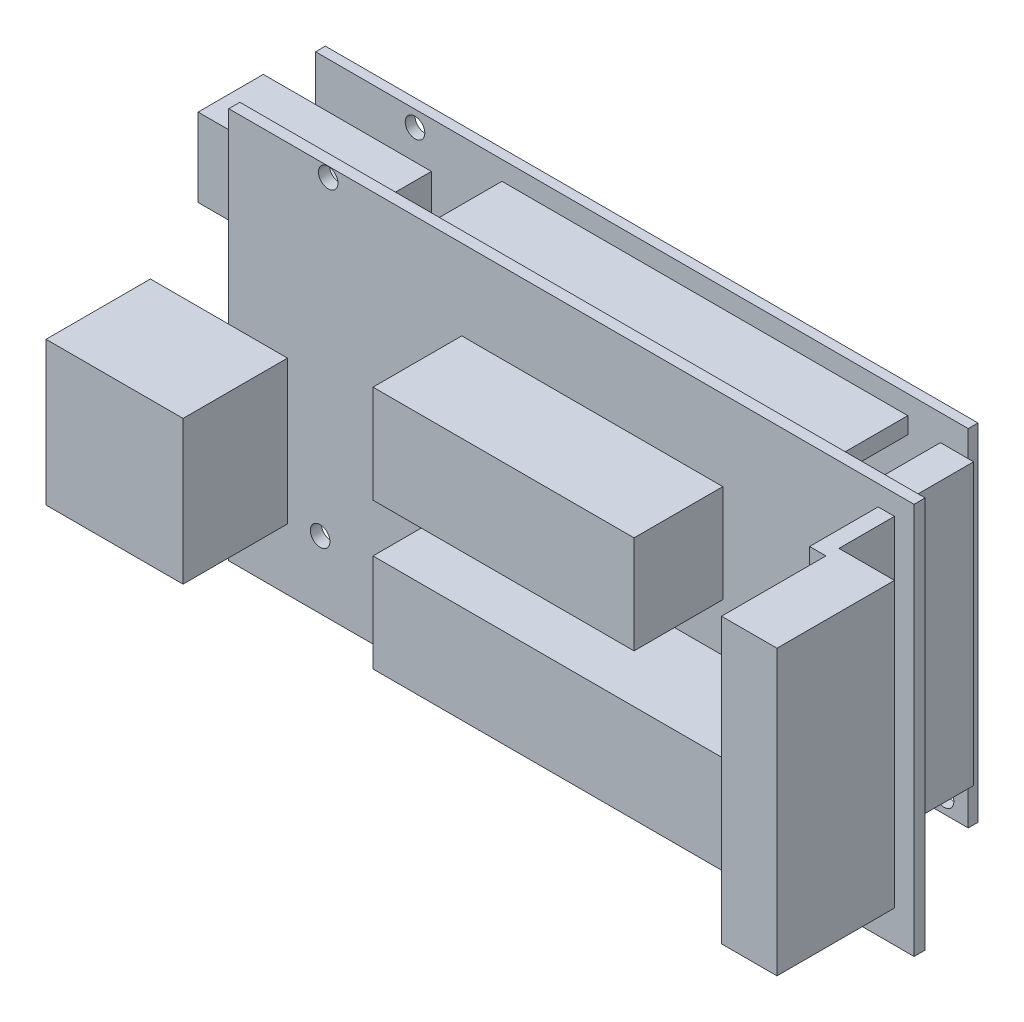
SolidWorks part; units mm, degrees
ref_plane "Plano frontal" through (0, 0, 0) normal (0, 0, 1) x (1, 0, 0)
ref_plane "Plano superior" through (0, 0, 0) normal (0, 1, 0) x (1, 0, 0)
ref_plane "Plano direito" through (0, 0, 0) normal (1, 0, 0) x (0, 0, -1)
sketch "Esboço1" plane through (0, 0, 0) normal (0, 0, 1) x (1, 0, 0)
  line L1 (-52.5, 30) -> (52.5, 30)
  line L2 (-52.5, 30) -> (-52.5, -30)
  line L3 (-52.5, -30) -> (52.5, -30)
  line L4 (52.5, 30) -> (52.5, -30)
  line L5 (-52.5, 30) -> (52.5, -30) construction
  line L6 (-52.5, -30) -> (52.5, 30) construction
  point P0 (0, 0)
  dimension "D1" = 60
  dimension "D2" = 105
extrude "Ressalto-extrusão1" add sketch "Esboço1" along normal blind 1.7
sketch "Esboço2" plane through (0, 0, 1.7) normal (0, 0, 1) x (1, 0, 0)
  line L0 (-52.5, -30) -> (52.5, -30) construction
  line L1 (-16.8, -4.7) -> (43.2, -4.7)
  line L2 (-16.8, -4.7) -> (-16.8, -19.7)
  line L3 (-16.8, -19.7) -> (43.2, -19.7)
  line L4 (43.2, -4.7) -> (43.2, -19.7)
  line L5 (52.5, -30) -> (52.5, 30) construction
  line L7 (-16.8, 2.7) -> (23.2, 2.7)
  line L8 (-16.8, 2.7) -> (-16.8, 17.7)
  line L9 (-16.8, 17.7) -> (23.2, 17.7)
  line L10 (23.2, 2.7) -> (23.2, 17.7)
  dimension "D1" = 60
  dimension "D2" = 15
  dimension "D3" = 10.3
  dimension "D4" = 9.3
  dimension "D5" = 40
  dimension "D6" = 7.4
extrude "Ressalto-extrusão2" add sketch "Esboço2" along normal blind 13.6
sketch "Esboço3" plane through (0, 0, 0) normal (0, 0, -1) x (-1, 0, 0)
  line L0 (52.5, -30) -> (-52.5, -30) construction
  line L1 (52.5, 30.9) -> (-47.5, 30.9)
  line L2 (52.5, 30.9) -> (52.5, -22.1)
  line L3 (52.5, -22.1) -> (-47.5, -22.1)
  line L4 (-47.5, 30.9) -> (-47.5, -22.1)
  line L5 (52.5, 30) -> (52.5, -30) construction
  dimension "D1" = 7.9
  dimension "D2" = 53
  dimension "D3" = 100
extrude "Ressalto-extrusão6" add sketch "Esboço3" along normal blind 1.5 from offset 11.6 separate body
sketch "Esboço4" plane through (0, 0, -11.6) normal (0, 0, 1) x (1, 0, 0)
  line L1 (-23.9415, 27.9898) -> (38.2426, 27.9898)
  line L2 (-23.9415, 27.9898) -> (-23.9415, 25.4498)
  line L3 (-23.9415, 25.4498) -> (38.2426, 25.4498)
  line L4 (38.2426, 27.9898) -> (38.2426, 25.4498)
  line L5 (48.3249, 26.9052) -> (43.2449, 26.9052)
  line L6 (48.3249, 26.9052) -> (48.3249, -16.0526)
  line L7 (48.3249, -16.0526) -> (43.2449, -16.0526)
  line L8 (43.2449, 26.9052) -> (43.2449, -16.0526)
  line L9 (38.2426, -19.9599) -> (-17.8292, -19.9599)
  line L10 (38.2426, -19.9599) -> (38.2426, -17.4199)
  line L11 (38.2426, -17.4199) -> (-17.8292, -17.4199)
  line L12 (-17.8292, -19.9599) -> (-17.8292, -17.4199)
  dimension "D1" = 2.54
  dimension "D2" = 5.08
extrude "Ressalto-extrusão8" add sketch "Esboço4" along normal up to surface (11.6 mm away) up to face at (0, 0, 0)
sketch "Esboço6" plane through (0, 0, 1.7) normal (0, 0, 1) x (1, 0, 0)
  line L1 (-64.5, 1.4) -> (-43.5, 1.4)
  line L2 (-64.5, 1.4) -> (-64.5, -20.6)
  line L3 (-64.5, -20.6) -> (-43.5, -20.6)
  line L4 (-43.5, 1.4) -> (-43.5, -20.6)
  line L5 (-52.5, 30) -> (-52.5, -30) construction
  line L6 (-52.5, 30.9) -> (47.5, 30.9) construction
  dimension "D1" = 22
  dimension "D2" = 29.5
  dimension "D3" = 12
  dimension "D4" = 21
extrude "Ressalto-extrusão9" add sketch "Esboço6" along normal blind 16
sketch "Esboço7" plane through (0, 0, -11.6) normal (0, 0, 1) x (1, 0, 0)
  line L0 (-52.5, 30.9) -> (47.5, 30.9) construction
  line L1 (-34.753, 23.9) -> (-60.5, 23.9)
  line L2 (-34.753, 23.9) -> (-34.753, 11.9)
  line L3 (-34.753, 11.9) -> (-60.5, 11.9)
  line L4 (-60.5, 23.9) -> (-60.5, 11.9)
  line L5 (-52.5, -22.1) -> (-52.5, 30.9) construction
  dimension "D1" = 7
  dimension "D2" = 12
  dimension "D3" = 8
extrude "Ressalto-extrusão10" add sketch "Esboço7" along normal blind 10
sketch "Esboço8" plane through (0, 0, -13.1) normal (0, 0, -1) x (-1, 0, 0)
  line L0 (52.5, -22.1) -> (52.5, 30.9) construction
  line L1 (-47.5, -22.1) -> (52.5, -22.1) construction
  circle A0 centre (37.26, 28.47) radius 1.5
  circle A1 centre (38.5, -19.7) radius 1.5
  circle A2 centre (-43.8, -19.7) radius 1.5
  dimension "D1" = 3
  dimension "D2" = 15.24
  dimension "D3" = 14
  dimension "D4" = 82.3
  dimension "D5" = 2.4
  dimension "D6" = 2.4
  dimension "D7" = 48.17
extrude "Corte-extrusão1" cut sketch "Esboço8" against normal through all
sketch "Esboço9" plane through (0, -30, 0) normal (0, -1, 0) x (1, 0, 0)
  line L0 (49.5, 1.7) -> (49.5, 10.2)
  line L1 (-52.5, 1.7) -> (52.5, 1.7) construction
  line L2 (49.5, 10.2) -> (58, 10.2)
  line L3 (58, 10.2) -> (58, 28.2)
  line L4 (58, 28.2) -> (49.5, 28.2)
  line L5 (49.5, 28.2) -> (49.5, 12.2)
  line L6 (47, 1.7) -> (49.5, 1.7)
  line L7 (49.5, 12.2) -> (47, 12.2)
  line L8 (47, 12.2) -> (47, 1.7)
  line L12 (47.5, -13.1) -> (47.5, -11.6) construction
  dimension "D1" = 8.5
  dimension "D2" = 18
  dimension "D3" = 8.5
  dimension "D4" = 2.5
  dimension "D5" = 0.5
  dimension "D6" = 8.5
  dimension "D7" = 2
extrude "Ressalto-extrusão11" add sketch "Esboço9" against normal up to surface (56.9052 mm away) up to face at (46.1279, 26.9052, -6.96)
sketch "Esboço10" plane through (58, 0, 0) normal (1, 0, 0) x (0, 0, -1)
  line L0 (-10.2, 26.9052) -> (-10.2, -30) construction
  line L1 (-10.2, -16.5737) -> (-28.2, -16.5737)
  line L2 (-10.2, -16.5737) -> (-10.2, 27.4263) construction
  line L3 (-10.2, 27.4263) -> (-28.2, 27.4263) construction
  line L4 (-28.2, -16.5737) -> (-28.2, 27.4263) construction
  line L5 (-10.2, -16.5737) -> (-28.2, 27.4263) construction
  line L6 (-10.2, 27.4263) -> (-28.2, -16.5737) construction
  line L7 (11.6, -16.0526) -> (11.6, 26.9052) construction
  line L8 (-28.2, 26.9052) -> (-28.2, -30) construction
  line L9 (-28.2, -16.5737) -> (-28.2, -30)
  line L10 (-28.2, -30) -> (-1.7, -30)
  line L11 (-10.2, -16.5737) -> (-1.7, -16.5737)
  line L12 (-1.7, -16.5737) -> (-1.7, -30)
  point P0 (-19.2, 5.4263)
  point P10 (11.6, 5.4263)
  dimension "D1" = 44
extrude "Corte-extrusão2" cut sketch "Esboço10" against normal up to surface (11 mm away) up to face at (47, -1.5474, 6.95)
equation "\"D5@Esboço2\"=\"D1@Esboço2\"*2/3"
equation "\"D2@Esboço4\"=\"D1@Esboço4\"*2"
